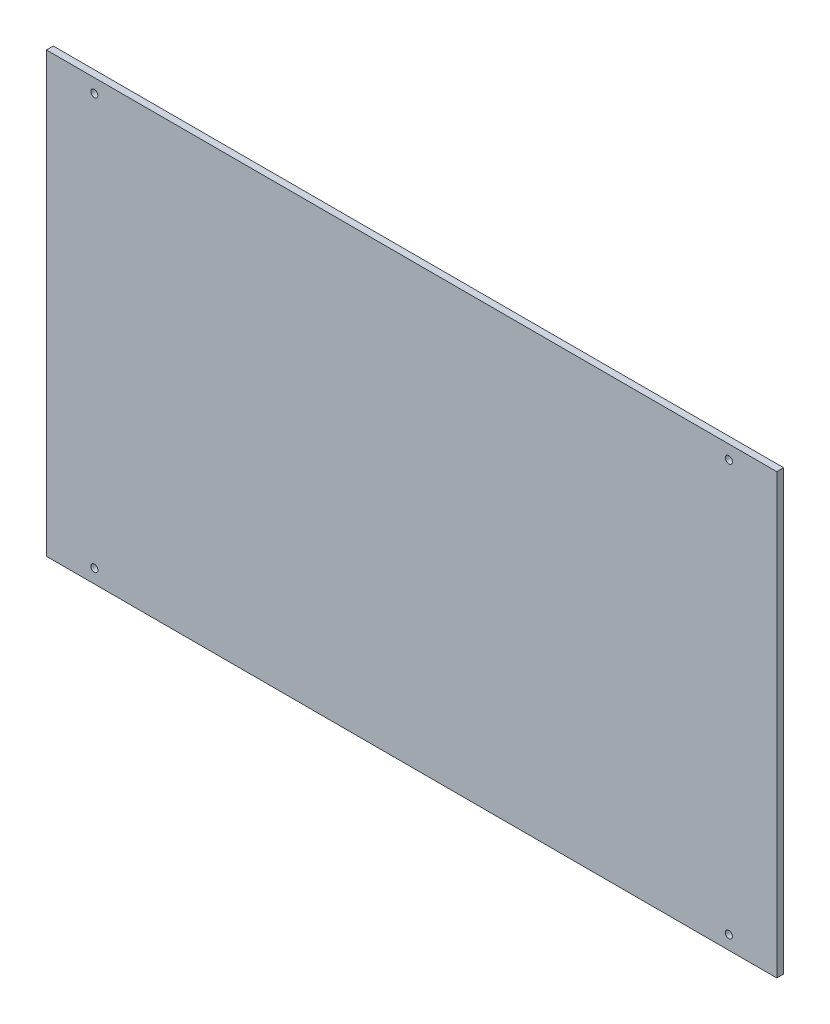
SolidWorks part; units mm, degrees
ref_plane "前视基准面" through (0, 0, 0) normal (0, 0, 1) x (1, 0, 0)
ref_plane "上视基准面" through (0, 0, 0) normal (0, 1, 0) x (1, 0, 0)
ref_plane "右视基准面" through (0, 0, 0) normal (1, 0, 0) x (0, 0, -1)
sketch "草图1" plane through (0, 0, 0) normal (0, 0, 1) x (1, 0, 0)
  line L0 (0, 0) -> (0, 320)
  line L1 (0, 320) -> (533, 320)
  line L2 (533, 320) -> (533, 0)
  line L3 (533, 0) -> (0, 0)
  circle A0 centre (35, 310) radius 2.6
  circle A1 centre (498, 310) radius 2.6
  circle A2 centre (498, 10) radius 2.6
  circle A4 centre (35, 10) radius 2.6
  point P11 (0, 0)
  point P19 (0, 0)
  dimension "D4" = 5.2
  dimension "D6" = 2
  dimension "D7" = 2
  dimension "D13" = 35
  dimension "D1" = 320
  dimension "D2" = 533
  dimension "D3" = 35
  dimension "D5" = 10
  dimension "D8" = 35
  dimension "D9" = 35
  dimension "D10" = 10
  dimension "D11" = 10
  dimension "D12" = 10
extrude "凸台-拉伸1" add sketch "草图1" along normal blind 5
